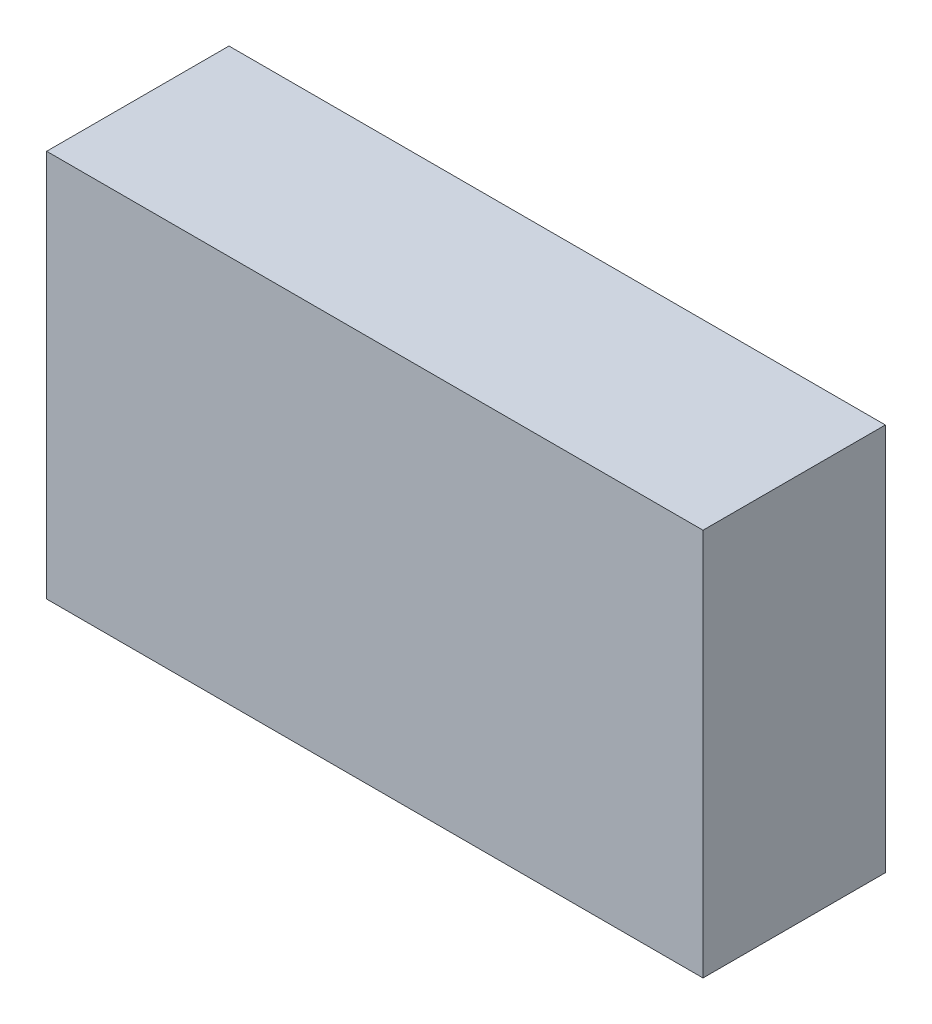
SolidWorks part; units mm, degrees
ref_plane "Front Plane" through (0, 0, 0) normal (0, 0, 1) x (1, 0, 0)
ref_plane "Top Plane" through (0, 0, 0) normal (0, 1, 0) x (1, 0, 0)
ref_plane "Right Plane" through (0, 0, 0) normal (1, 0, 0) x (0, 0, -1)
sketch "Sketch1" plane through (0, 0, 0) normal (0, 0, 1) x (1, 0, 0)
  line L0 (-1.8, 1.0635) -> (1.8, 1.0635)
  line L1 (1.8, 1.0635) -> (1.8, -1.0635)
  line L2 (1.8, -1.0635) -> (-1.8, -1.0635)
  line L3 (-1.8, -1.0635) -> (-1.8, 1.0635)
extrude "Component_Outline" add sketch "Sketch1" along normal blind 1 separate body
sketch3d "3DSketch1"
  line L0 (0, 0, 0) -> (1, 0, 0)
  line L1 (0, 0, 0) -> (0, 1, 0)
  line L2 (0, 0, 0) -> (0, 0, 1)
  point P0 (0, 0, 0)
